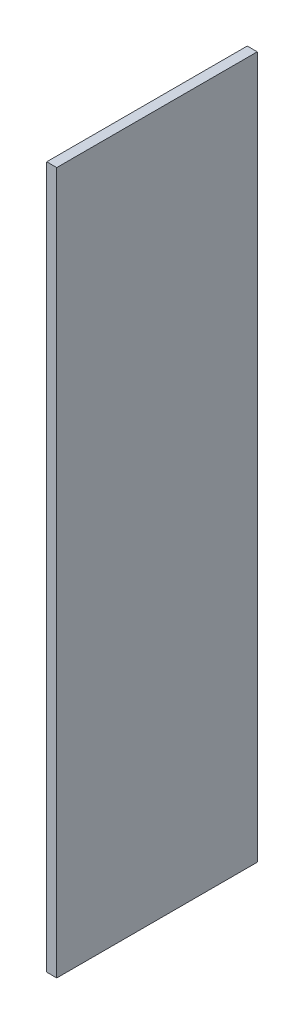
SolidWorks part; units mm, degrees
ref_plane "Alzado" through (0, 0, 0) normal (0, 0, 1) x (1, 0, 0)
ref_plane "Planta" through (0, 0, 0) normal (0, 1, 0) x (1, 0, 0)
ref_plane "Vista lateral" through (0, 0, 0) normal (1, 0, 0) x (0, 0, -1)
sketch "Croquis1" plane through (0, 0, 0) normal (0, 0, 1) x (1, 0, 0)
  line L1 (0, 0) -> (10, 0)
  line L2 (0, 0) -> (0, 700)
  line L3 (0, 700) -> (10, 700)
  line L4 (10, 0) -> (10, 700)
  dimension "D1" = 10
  dimension "D2" = 700
extrude "Saliente-Extruir1" add sketch "Croquis1" along normal blind 200
sketch "Croquis3" plane through (10, 0, 0) normal (1, 0, 0) x (0, 0, -1)
  circle A0 centre (-100, 110) radius 10
  circle A1 centre (-100, 230) radius 10
  circle A2 centre (-100, 350) radius 10
  circle A3 centre (-100, 470) radius 10
  circle A4 centre (-100, 590) radius 10
